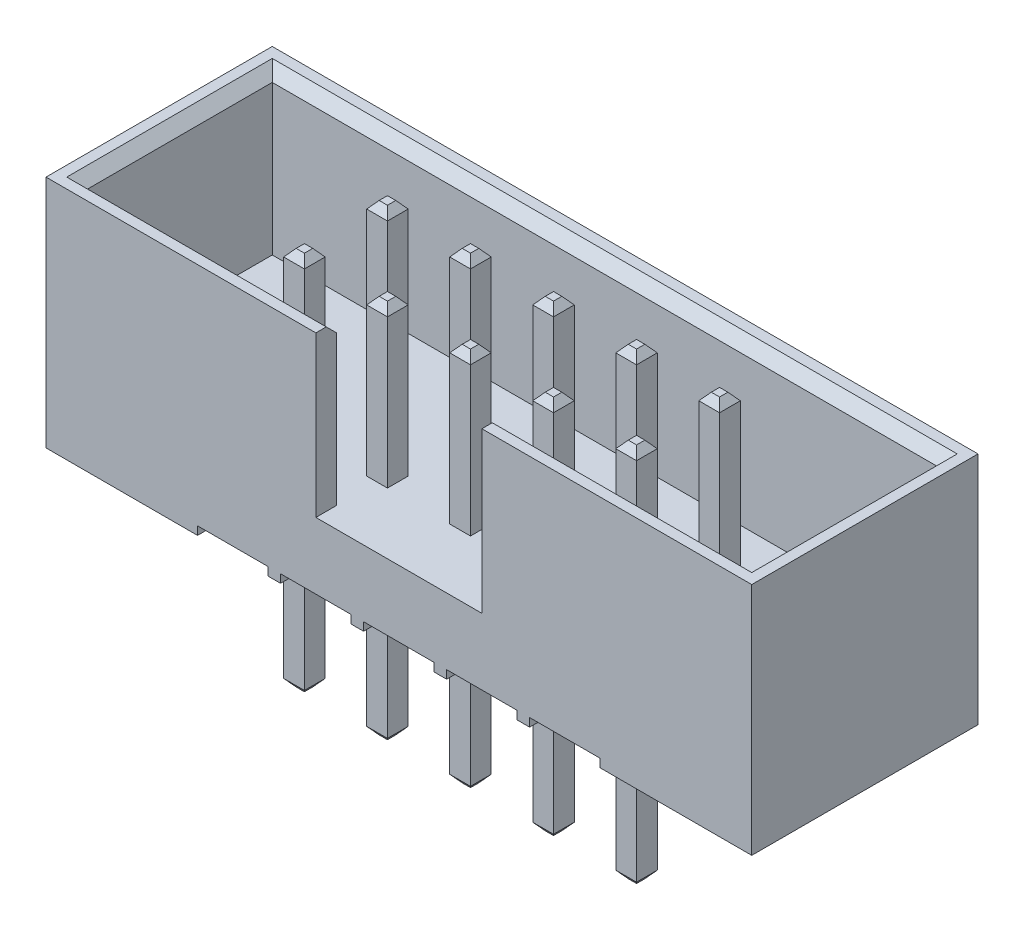
SolidWorks part; units mm, degrees
ref_plane "Спереди" through (0, 0, 0) normal (0, 0, 1) x (1, 0, 0)
ref_plane "Сверху" through (0, 0, 0) normal (0, 1, 0) x (1, 0, 0)
ref_plane "Справа" through (0, 0, 0) normal (1, 0, 0) x (0, 0, -1)
ref_plane "Плоскость1" through (0, -3.6, 0) normal (0, 1, 0) x (1, 0, 0)
sketch "Эскиз1" plane through (0, 0, 0) normal (0, 1, 0) x (1, 0, 0)
  line L1 (0, 0) -> (17, 0)
  line L2 (0, 0) -> (0, 5.45)
  line L3 (0, 5.45) -> (17, 5.45)
  line L4 (17, 0) -> (17, 5.45)
  dimension "D1" = 5.45
  dimension "A" = 17
extrude "Корпус" add sketch "Эскиз1" along normal blind 5.65
sketch "Эскиз6" plane through (0, 0, 0) normal (0, 0, 1) x (1, 0, 0)
  line L0 (0, 5.65) -> (0, 0) construction
  line L1 (3.65, 0) -> (5.35, 0)
  line L2 (3.65, 0) -> (3.65, 0.2)
  line L3 (3.65, 0.2) -> (5.35, 0.2)
  line L4 (5.35, 0) -> (5.35, 0.2)
  line L5 (3.65, 0) -> (5.35, 0.2) construction
  line L6 (3.65, 0.2) -> (5.35, 0) construction
  line L7 (0, 0) -> (17, 0) construction
  point P0 (4.5, 0.1)
  dimension "D1" = 1.7
  dimension "D2" = 4.5
  dimension "D3" = 0.2
extrude "Вырез-Вытянуть7" cut sketch "Эскиз6" against normal through all
pattern_linear "Линейный массив3" count 5 spacing 2 along (1, 0, 0) of "Вырез-Вытянуть7"
sketch "Эскиз2" plane through (0, 5.65, 0) normal (0, 1, 0) x (1, 0, 0)
  line L0 (0, 5.45) -> (0, 0) construction
  line L1 (0.5, 0.5) -> (16.5, 0.5)
  line L2 (0.5, 0.5) -> (0.5, 4.95)
  line L3 (0.5, 4.95) -> (16.5, 4.95)
  line L4 (17, 5.45) -> (0, 5.45) construction
  line L7 (0, 0) -> (17, 0) construction
  line L8 (17, 0) -> (17, 5.45) construction
  line L12 (16.5, 0.5) -> (16.5, 4.95)
  dimension "D2" = 0.5
  dimension "D3" = 0.5
  dimension "D4" = 0.5
  dimension "D1" = 0.5
extrude "Вырез-Вытянуть2" cut sketch "Эскиз2" against normal offset from surface (3.85 mm away) 1.8 up to face at (15.175, 0, -2.725)
sketch "Эскиз3" plane through (0, 0, 0) normal (0, 0, 1) x (1, 0, 0)
  line L0 (0, 5.65) -> (17, 5.65) construction
  line L1 (6.5, 1.8) -> (10.5, 1.8)
  line L2 (6.5, 1.8) -> (6.5, 5.65)
  line L3 (6.5, 5.65) -> (10.5, 5.65)
  line L4 (10.5, 1.8) -> (10.5, 5.65)
  line L5 (6.5, 1.8) -> (10.5, 5.65) construction
  line L6 (6.5, 5.65) -> (10.5, 1.8) construction
  line L9 (8.5, 5.65) -> (8.5, 1.8) construction
  line L10 (0, 5.65) -> (0, 0) construction
  line L11 (17, 5.65) -> (17, 0) construction
  line L12 (0.5, 1.8) -> (16.5, 1.8) construction
  point P0 (8.5, 3.725)
  dimension "D1" = 4
extrude "Вырез-Вытянуть3" cut sketch "Эскиз3" against normal up to next
sketch "Эскиз5" plane through (0, -3.6, 0) normal (0, 1, 0) x (1, 0, 0)
  line L0 (4.25, 1.975) -> (4.5, 1.725) construction
  line L1 (4.25, 3.975) -> (4.5, 3.725) construction
  line L2 (4.5, 3.725) -> (4.75, 3.475) construction
  line L3 (4.5, 1.725) -> (4.75, 1.475) construction
  line L6 (0, 0) -> (6.5, 0) construction
  line L9 (4.25, 1.975) -> (4.75, 1.975)
  line L10 (4.25, 1.975) -> (4.25, 1.475)
  line L11 (4.25, 1.475) -> (4.75, 1.475)
  line L12 (4.75, 1.975) -> (4.75, 1.475)
  line L14 (4.25, 1.475) -> (4.75, 1.975) construction
  line L15 (4.25, 3.975) -> (4.75, 3.975)
  line L16 (4.25, 3.975) -> (4.25, 3.475)
  line L17 (4.25, 3.475) -> (4.75, 3.475)
  line L18 (4.75, 3.975) -> (4.75, 3.475)
  line L20 (4.25, 3.475) -> (4.75, 3.975) construction
  line L24 (0, 5.45) -> (0, 0) construction
  point P0 (4.5, 1.725)
  dimension "D1" = 0.5
  dimension "D2" = 2
  dimension "D3" = 4.5
  dimension "D4" = 1.725
extrude "Контакты" add sketch "Эскиз5" along normal offset from surface (9.15 mm away) 0.1 up to face at (8.5, 5.65, -1.9)
chamfer "Фаска (корпус)" distance 0.25 angle 45 5 edges at (13.5, 5.65, -0.5) (16.5, 5.65, -2.725) (3.5, 5.65, -0.5) (0.5, 5.65, -2.725) (8.5, 5.65, -4.95)
chamfer "Фаска (контакты)" distance 0.15 angle 50 16 edges at (4.5, -3.6, -3.975) (4.25, -3.6, -3.725) (4.5, -3.6, -3.475) (4.75, -3.6, -3.725) (4.5, -3.6, -1.975) (4.25, -3.6, -1.725) (4.5, -3.6, -1.475) (4.75, -3.6, -1.725) (4.75, 5.55, -3.725) (4.5, 5.55, -3.475) (4.25, 5.55, -3.725) (4.5, 5.55, -3.975) (4.75, 5.55, -1.725) (4.5, 5.55, -1.475) (4.25, 5.55, -1.725) (4.5, 5.55, -1.975)
pattern_linear "Линейный массив2" count 5 spacing 2 along (1, 0, 0) of "Контакты", "Фаска (контакты)"
